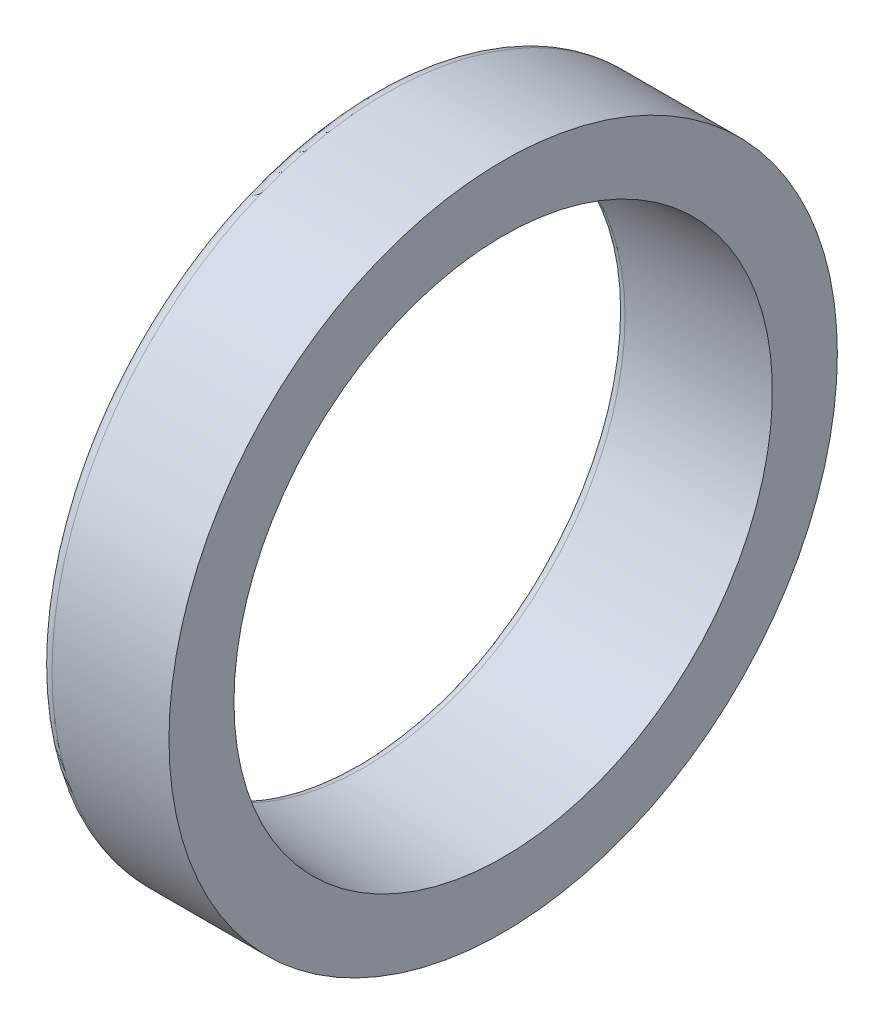
SolidWorks part; units mm, degrees
ref_plane "Płaszczyzna przednia" through (0, 0, 0) normal (0, 0, 1) x (1, 0, 0)
ref_plane "Płaszczyzna górna" through (0, 0, 0) normal (0, 1, 0) x (1, 0, 0)
ref_plane "Płaszczyzna prawa" through (0, 0, 0) normal (1, 0, 0) x (0, 0, -1)
sketch "Szkic1" plane through (0, 0, 0) normal (0, 0, 1) x (1, 0, 0)
  line L0 (1, 18) -> (1, 14.5)
  line L1 (1, 14.5) -> (-7, 14)
  line L2 (-7, 14) -> (-7, 15)
  line L3 (-7, 15) -> (-5.2201, 15.2046)
  line L4 (1, 18) -> (-5.3, 18)
  line L5 (1, 18) -> (-6, 18) construction
  line L6 (-14.0214, 0) -> (4.5246, 0) construction
  line L7 (-6, 22) -> (-6, -22) construction
  arc A0 (-5.3, 18) -> (-5.3, 16.6) centre (-5.3, 17.3) ccw
  arc A1 (-5.3, 16.6) -> (-5.2201, 15.2046) centre (-5.3, 15.9) cw
  dimension "D1" = 0.7
  dimension "D2" = 0.7
  dimension "D3" = 28
  dimension "D4" = 8
  dimension "D5" = 1
revolve "Obrót1" add sketch "Szkic1" angle 360 about L6
fillet "Zaokrąglenie1" radius 0.5 2 edges at (-7, 0, 14) (-7, 0, 15)
